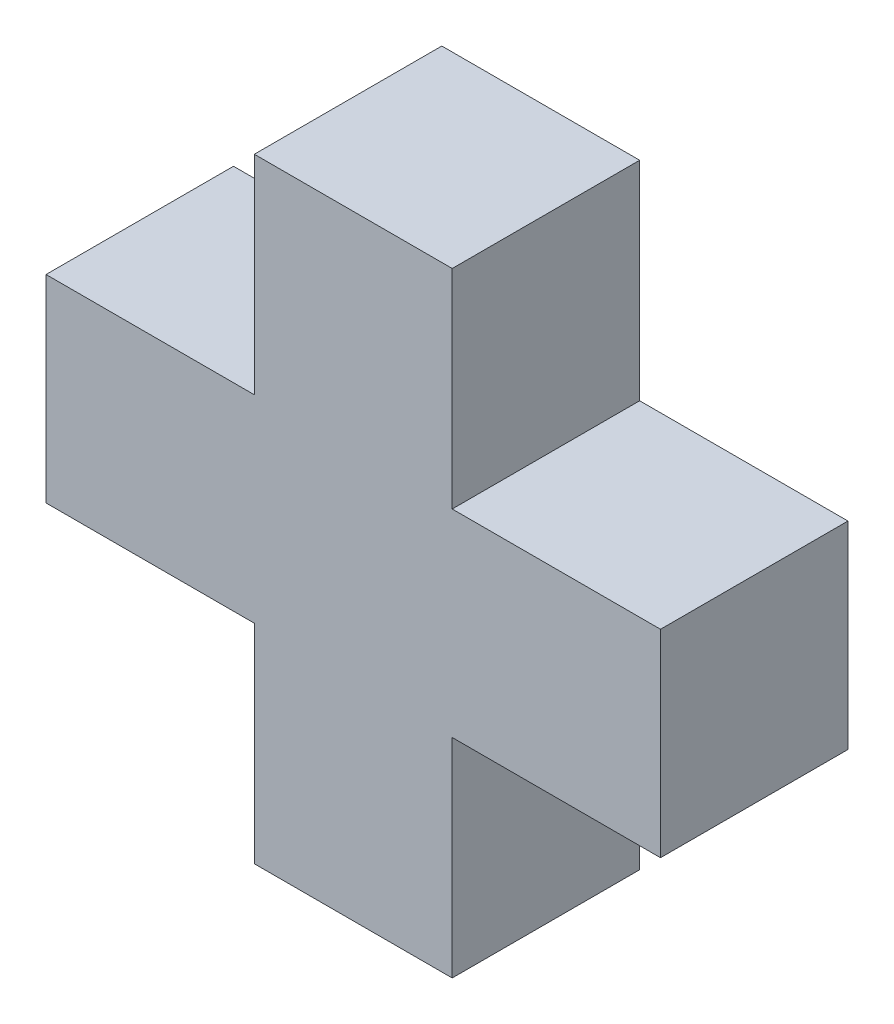
SolidWorks part; units mm, degrees
ref_plane "Front Plane" through (0, 0, 0) normal (0, 0, 1) x (1, 0, 0)
ref_plane "Top Plane" through (0, 0, 0) normal (0, 1, 0) x (1, 0, 0)
ref_plane "Right Plane" through (0, 0, 0) normal (1, 0, 0) x (0, 0, -1)
sketch "Sketch1" plane through (0, 0, 0) normal (0, 0, 1) x (1, 0, 0)
  line L1 (-4.75, -14.75) -> (4.75, -14.75)
  line L2 (-4.75, -14.75) -> (-4.75, -4.75)
  line L3 (-4.75, 14.75) -> (4.75, 14.75)
  line L4 (4.75, -14.75) -> (4.75, -4.75)
  line L5 (-4.75, -14.75) -> (4.75, 14.75) construction
  line L6 (-4.75, 14.75) -> (4.75, -14.75) construction
  line L7 (-14.75, -4.75) -> (-4.75, -4.75)
  line L8 (-14.75, -4.75) -> (-14.75, 4.75)
  line L9 (-14.75, 4.75) -> (-4.75, 4.75)
  line L10 (14.75, -4.75) -> (14.75, 4.75)
  line L11 (-14.75, -4.75) -> (14.75, 4.75) construction
  line L12 (-14.75, 4.75) -> (14.75, -4.75) construction
  line L13 (-4.75, 4.75) -> (-4.75, 14.75)
  line L14 (4.75, 4.75) -> (14.75, 4.75)
  line L15 (4.75, 4.75) -> (4.75, 14.75)
  line L17 (4.75, -4.75) -> (14.75, -4.75)
  point P0 (0, 0)
  point P6 (0, 0)
  dimension "D1" = 10
  dimension "D3" = 10
  dimension "D4" = 9.5
extrude "Boss-Extrude2" add sketch "Sketch1" along normal blind 9
